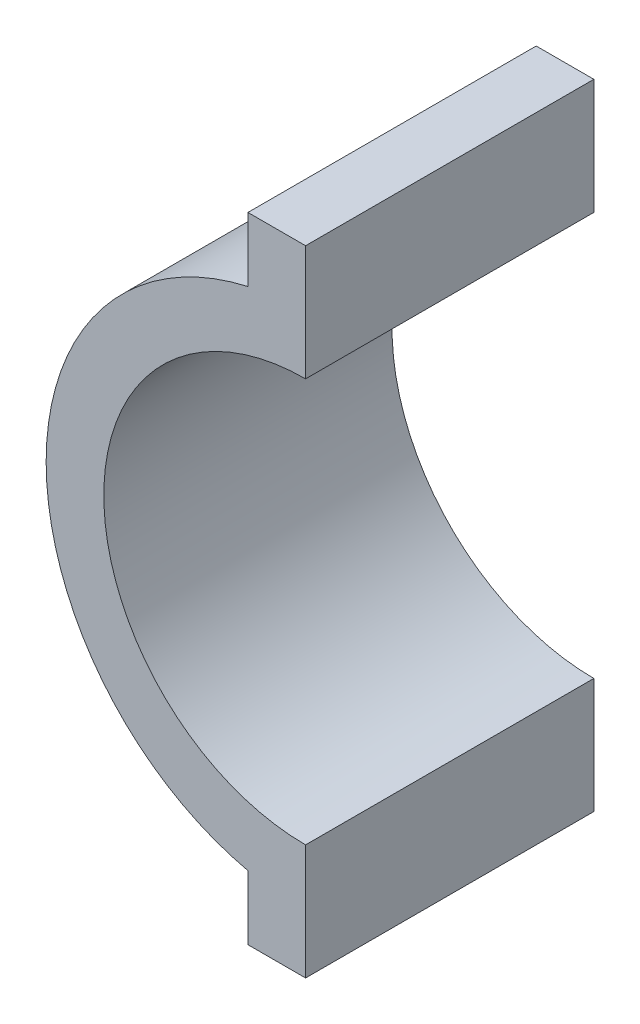
SolidWorks part; units mm, degrees
ref_plane "Front Plane" through (0, 0, 0) normal (0, 0, 1) x (1, 0, 0)
ref_plane "Top Plane" through (0, 0, 0) normal (0, 1, 0) x (1, 0, 0)
ref_plane "Right Plane" through (0, 0, 0) normal (1, 0, 0) x (0, 0, -1)
sketch "Sketch4" plane through (0, 0, 0) normal (0, 0, 1) x (1, 0, 0)
  line L0 (0, 22.5) -> (0, 17.5)
  line L1 (0, 22.5) -> (0, 27.5)
  line L2 (0, -22.5) -> (0, -27.5)
  line L3 (-5, 22.5) -> (-5, 27.5)
  line L4 (-5, 22.5) -> (-5, 21.9374)
  line L5 (-5, -22.5) -> (-5, -27.5)
  line L6 (-5, 27.5) -> (0, 27.5)
  line L7 (-5, -27.5) -> (0, -27.5)
  line L8 (0, -17.5) -> (0, -22.5)
  line L9 (-5, -21.9374) -> (-5, -22.5)
  line L10 (0, 22.5) -> (0, -22.5) construction
  line L12 (-5, 22.5) -> (-5, -22.5) construction
  arc A0 (0, 17.5) -> (0, -17.5) centre (0, 0) ccw
  arc A1 (-5, 21.9374) -> (-5, -21.9374) centre (0, 0) ccw
  circle A3 centre (0, 0) radius 22.5 construction
  circle A4 centre (0, 0) radius 17.5 construction
  point P4 (16.7353, 5.1165)
  point P13 (22.5, 0)
  dimension "D1" = 35
  dimension "D2" = 5
extrude "Boss-Extrude1" add sketch "Sketch4" along normal blind 25
